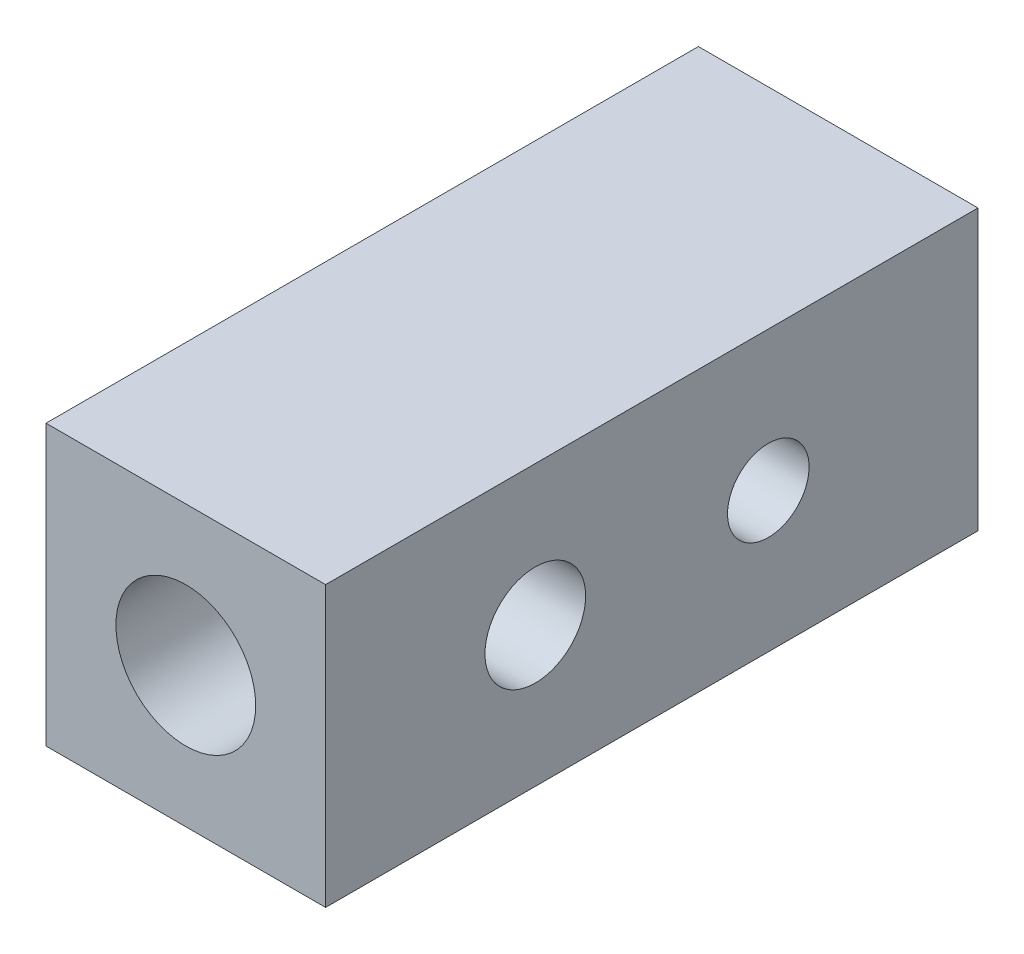
SolidWorks part; units mm, degrees
material "6061-T6 (SS)"
ref_plane "Front Plane" through (0, 0, 0) normal (0, 0, 1) x (1, 0, 0)
ref_plane "Top Plane" through (0, 0, 0) normal (0, 1, 0) x (1, 0, 0)
ref_plane "Right Plane" through (0, 0, 0) normal (1, 0, 0) x (0, 0, -1)
sketch "Sketch1" plane through (0, 0, 0) normal (0, 0, 1) x (1, 0, 0)
  line L1 (-19.05, 19.05) -> (19.05, 19.05)
  line L2 (-19.05, 19.05) -> (-19.05, -19.05)
  line L3 (-19.05, -19.05) -> (19.05, -19.05)
  line L4 (19.05, 19.05) -> (19.05, -19.05)
  line L5 (-19.05, 19.05) -> (19.05, -19.05) construction
  line L6 (-19.05, -19.05) -> (19.05, 19.05) construction
  circle A0 centre (0, 0) radius 9.525
  point P0 (0, 0)
  dimension "D3" = 19.05
  dimension "D1" = 38.1
  dimension "D2" = 38.1
extrude "Boss-Extrude1" add sketch "Sketch1" along normal mid plane 88.9
sketch "Sketch2" plane through (19.05, 0, 0) normal (1, 0, 0) x (0, 0, -1)
  line L0 (-44.45, 0) -> (-15.875, 0) construction
  line L1 (-44.45, -19.05) -> (-44.45, 19.05) construction
  line L2 (-15.875, 0) -> (15.875, 0) construction
  circle A0 centre (-15.875, 0) radius 6.858
  dimension "D3" = 13.716
  dimension "D1" = 28.575
  dimension "D2" = 60.325
extrude "Cut-Extrude1" cut sketch "Sketch2" against normal through all
sketch "Sketch3" plane through (19.05, 0, 0) normal (1, 0, 0) x (0, 0, -1)
  line L0 (44.45, -19.05) -> (44.45, 19.05) construction
  circle A0 centre (15.875, 0) radius 5.5562
  circle A1 centre (-15.875, 0) radius 6.858 construction
  dimension "D1" = 11.1125
  dimension "D2" = 31.75
  dimension "D3" = 28.575
extrude "Cut-Extrude2" cut sketch "Sketch3" against normal blind 19.05
sketch "Sketch4" plane through (-19.05, 0, 0) normal (-1, 0, 0) x (0, 0, 1)
  line L0 (-44.45, 19.05) -> (-44.45, -19.05) construction
  circle A0 centre (-15.875, 0) radius 6.858
  circle A1 centre (15.875, 0) radius 6.858 construction
  dimension "D1" = 13.716
  dimension "D2" = 31.75
  dimension "D3" = 28.575
extrude "Cut-Extrude3" cut sketch "Sketch4" against normal blind 19.05
